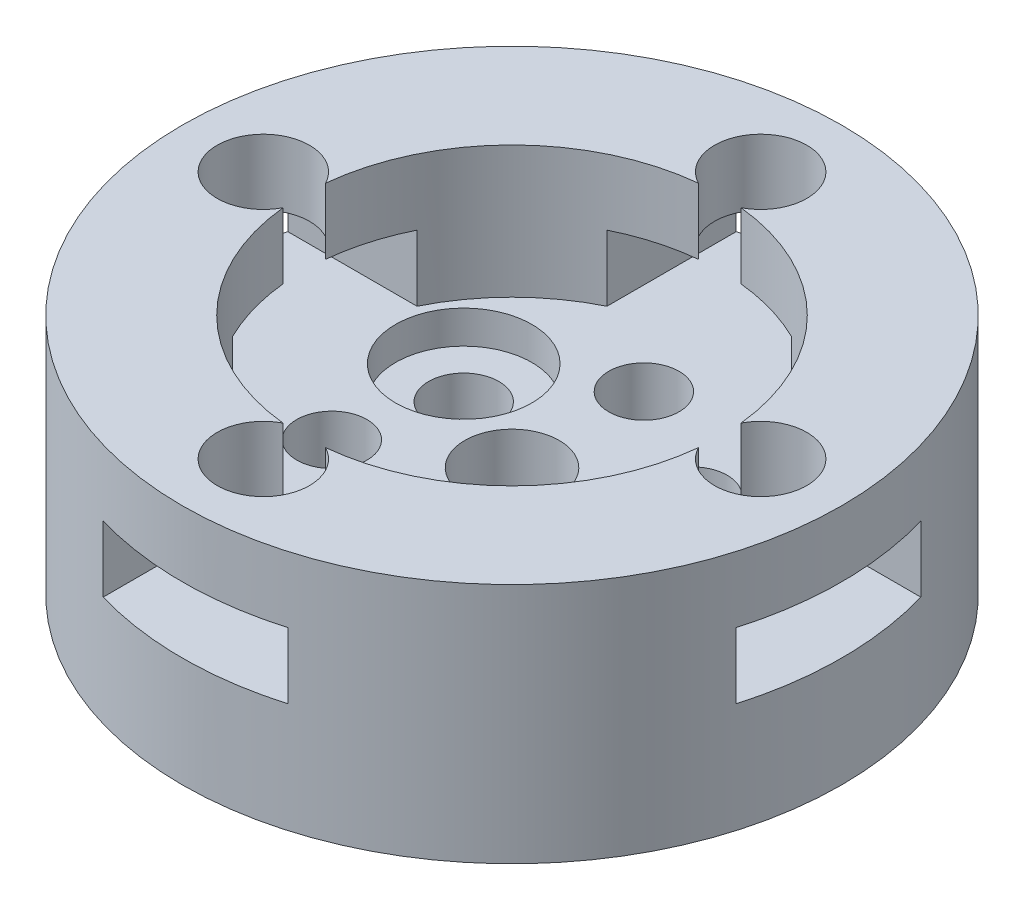
SolidWorks part; units mm, degrees
ref_plane "前视基准面" through (0, 0, 0) normal (0, 0, 1) x (1, 0, 0)
ref_plane "上视基准面" through (0, 0, 0) normal (0, 1, 0) x (1, 0, 0)
ref_plane "右视基准面" through (0, 0, 0) normal (1, 0, 0) x (0, 0, -1)
sketch "Sketch1" plane through (0, 0, 0) normal (0, 1, 0) x (1, 0, 0)
  line L0 (0, 11.2998) -> (0, -11.3131) construction
  circle A0 centre (0, 0) radius 10
  circle A1 centre (0, 0) radius 6 construction
  circle A2 centre (0, 6) radius 1.6
  circle A3 centre (5.1962, 3) radius 1.6
  circle A4 centre (5.1962, -3) radius 1.6
  circle A5 centre (0, -6) radius 1.6
  circle A6 centre (-5.1962, -3) radius 1.6
  circle A7 centre (-5.1962, 3) radius 1.6
  circle A8 centre (0, 0) radius 2.15
  point P7 (0, -6)
  dimension "D1" = 20
  dimension "D2" = 12
  dimension "D3" = 3.2
  dimension "D5" = 4.3
  dimension "D4" = 6
extrude "Boss-Extrude1" add sketch "Sketch1" along normal blind 5
sketch "Sketch2" plane through (0, 5, 0) normal (0, 1, 0) x (1, 0, 0)
  line L0 (0, 10.3978) -> (0, -10.7765) construction
  circle A0 centre (-5.1962, 3) radius 3.1
  circle A3 centre (5.1962, -3) radius 3.1
  circle A6 centre (0, 0) radius 6 construction
  circle A7 centre (0, 6) radius 3.1 [skipped]
  circle A8 centre (0, -6) radius 3.1 [skipped]
  circle A9 centre (-5.1962, -3) radius 3.1 [skipped]
  circle A10 centre (5.1962, 3) radius 3.1 [skipped]
  point P5 (0, -6)
  point P16 (0, 0)
  dimension "D1" = 6.2
  dimension "D2" = 6
extrude "Cut-Extrude2" cut sketch "Sketch2" against normal blind 1.5
sketch "Sketch3" plane through (0, 0, 0) normal (0, -1, 0) x (1, 0, 0)
  circle A0 centre (0, 0) radius 9.5
  circle A1 centre (0, 0) radius 15
  dimension "D1" = 30
  dimension "D2" = 19
extrude "Boss-Extrude2" add sketch "Sketch3" against normal blind 11
sketch "Sketch5" plane through (0, 11, 0) normal (0, 1, 0) x (1, 0, 0)
  line L0 (0, 16.1958) -> (0, -15.6011) construction
  line L1 (11.3137, 0) -> (0, 11.3137) construction
  line L2 (0, 11.3137) -> (-11.3137, 0) construction
  line L3 (-11.3137, 0) -> (0, -11.3137) construction
  line L4 (0, -11.3137) -> (11.3137, 0) construction
  circle A0 centre (0, 0) radius 8 construction
  circle A1 centre (0, 11.3137) radius 2.1
  circle A2 centre (11.3137, 0) radius 2.1
  circle A3 centre (0, -11.3137) radius 2.1
  circle A4 centre (-11.3137, 0) radius 2.1
  point P10 (0, 0)
  point P19 (0, 0)
  dimension "D1" = 16
  dimension "D2" = 4.2
  dimension "D3" = 4
extrude "Cut-Extrude3" cut sketch "Sketch5" against normal blind 3
sketch "Sketch7" plane through (0, 8, 0) normal (0, 1, 0) x (1, 0, 0)
  line L0 (0, 15.5155) -> (0, -16.6788) construction
  line L1 (-19.046, 0) -> (22.9688, 0) construction
  line L2 (-17.3137, 4.2) -> (-7.3137, 4.2)
  line L3 (-7.3137, 4.2) -> (-7.3137, -4.2)
  line L4 (-17.3137, 4.2) -> (-17.3137, -4.2)
  line L5 (-17.3137, -4.2) -> (-7.3137, -4.2)
  line L6 (4.2, 7.3137) -> (-4.2, 7.3137)
  line L7 (-4.2, 17.3137) -> (-4.2, 7.3137)
  line L8 (4.2, 17.3137) -> (-4.2, 17.3137)
  line L9 (4.2, 17.3137) -> (4.2, 7.3137)
  line L10 (7.3137, -4.2) -> (7.3137, 4.2)
  line L11 (17.3137, 4.2) -> (7.3137, 4.2)
  line L12 (17.3137, -4.2) -> (17.3137, 4.2)
  line L13 (17.3137, -4.2) -> (7.3137, -4.2)
  line L14 (-4.2, -7.3137) -> (4.2, -7.3137)
  line L15 (4.2, -17.3137) -> (4.2, -7.3137)
  line L16 (-4.2, -17.3137) -> (4.2, -17.3137)
  line L17 (-4.2, -17.3137) -> (-4.2, -7.3137)
  circle A0 centre (-11.3137, 0) radius 0.5 construction
  point P10 (-7.3137, 0)
  point P11 (-17.3137, 0)
  point P26 (0, 0)
  dimension "D5" = 1
  dimension "D1" = 4
  dimension "D2" = 4.2
  dimension "D3" = 10
  dimension "D4" = 4
extrude "Cut-Extrude4" cut sketch "Sketch7" against normal blind 3
